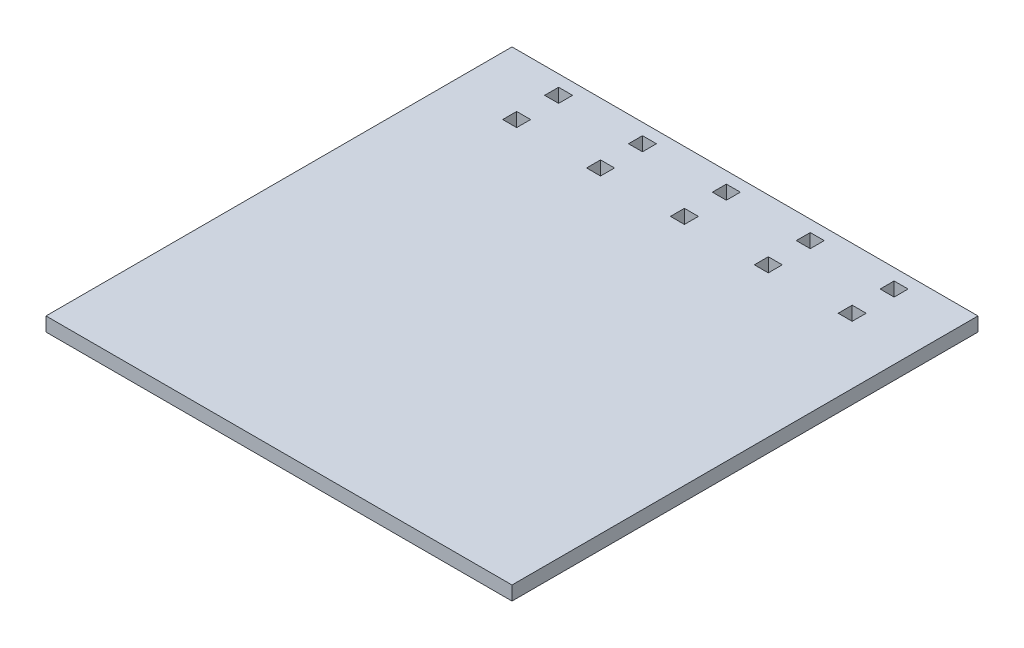
SolidWorks part; units mm, degrees
material "Maple"
ref_plane "Front Plane" through (0, 0, 0) normal (0, 0, 1) x (1, 0, 0)
ref_plane "Top Plane" through (0, 0, 0) normal (0, 1, 0) x (1, 0, 0)
ref_plane "Right Plane" through (0, 0, 0) normal (1, 0, 0) x (0, 0, -1)
sketch "Sketch2" plane through (0, 0, 0) normal (0, 1, 0) x (1, 0, 0)
  line L0 (0, 0) -> (-200, 0)
  line L1 (-200, 0) -> (-200, 200)
  line L2 (-200, 200) -> (0, 200)
  line L3 (0, 200) -> (0, 0)
  line L4 (-25, 195) -> (-31, 195)
  line L5 (-31, 195) -> (-31, 189)
  line L6 (-31, 189) -> (-25, 189)
  line L7 (-25, 189) -> (-25, 195)
  line L8 (-25, 177) -> (-31, 177)
  line L9 (-31, 177) -> (-31, 171)
  line L10 (-31, 171) -> (-25, 171)
  line L11 (-25, 171) -> (-25, 177)
  line L12 (-61, 195) -> (-67, 195)
  line L13 (-67, 195) -> (-67, 189)
  line L14 (-67, 189) -> (-61, 189)
  line L15 (-61, 189) -> (-61, 195)
  line L16 (-61, 177) -> (-67, 177)
  line L17 (-67, 177) -> (-67, 171)
  line L18 (-67, 171) -> (-61, 171)
  line L19 (-61, 171) -> (-61, 177)
  line L20 (-97, 195) -> (-103, 195)
  line L21 (-103, 195) -> (-103, 189)
  line L22 (-103, 189) -> (-97, 189)
  line L23 (-97, 189) -> (-97, 195)
  line L24 (-97, 177) -> (-103, 177)
  line L25 (-103, 177) -> (-103, 171)
  line L26 (-103, 171) -> (-97, 171)
  line L27 (-97, 171) -> (-97, 177)
  line L28 (-133, 195) -> (-139, 195)
  line L29 (-139, 195) -> (-139, 189)
  line L30 (-139, 189) -> (-133, 189)
  line L31 (-133, 189) -> (-133, 195)
  line L32 (-133, 177) -> (-139, 177)
  line L33 (-139, 177) -> (-139, 171)
  line L34 (-139, 171) -> (-133, 171)
  line L35 (-133, 171) -> (-133, 177)
  line L36 (-169, 195) -> (-175, 195)
  line L37 (-175, 195) -> (-175, 189)
  line L38 (-175, 189) -> (-169, 189)
  line L39 (-169, 189) -> (-169, 195)
  line L40 (-169, 177) -> (-175, 177)
  line L41 (-175, 177) -> (-175, 171)
  line L42 (-175, 171) -> (-169, 171)
  line L43 (-169, 171) -> (-169, 177)
  point P13 (-25, 192)
  point P14 (-61, 192)
  point P15 (-28, 177)
  point P24 (-61, 174)
  point P27 (-64, 195)
  point P46 (-133, 192)
  point P47 (-133, 174)
  point P49 (-103, 192)
  point P60 (-169, 174)
  point P62 (-172, 189)
  point P63 (-172, 177)
  dimension "D2" = 200
  dimension "D3" = 200
  dimension "D4" = 200
  dimension "D5" = 6
  dimension "D6" = 6
  dimension "D7" = 6
  dimension "D8" = 5
  dimension "D9" = 3
  dimension "D10" = 25
  dimension "D11" = 12
  dimension "D12" = 5
  dimension "D13" = 12
  dimension "D14" = 6
  dimension "D15" = 6
  dimension "D16" = 18
  dimension "D17" = 36
  dimension "D18" = 5
  dimension "D19" = 6
  dimension "D20" = 12
  dimension "D21" = 30
  dimension "D22" = 30
  dimension "D23" = 36
  dimension "D24" = 6
  dimension "D25" = 6
  dimension "D26" = 6
  dimension "D27" = 6
  dimension "D28" = 6
  dimension "D29" = 12
  dimension "D30" = 6
  dimension "D31" = 6
  dimension "D32" = 30
  dimension "D33" = 6
  dimension "D34" = 6
  dimension "D35" = 6
  dimension "D36" = 6
  dimension "D37" = 12
  dimension "D38" = 30
  dimension "D39" = 6
  dimension "D40" = 25
  dimension "D41" = 30
  dimension "D42" = 5
  dimension "D43" = 5
extrude "Boss-Extrude1" add sketch "Sketch2" along normal blind 6
